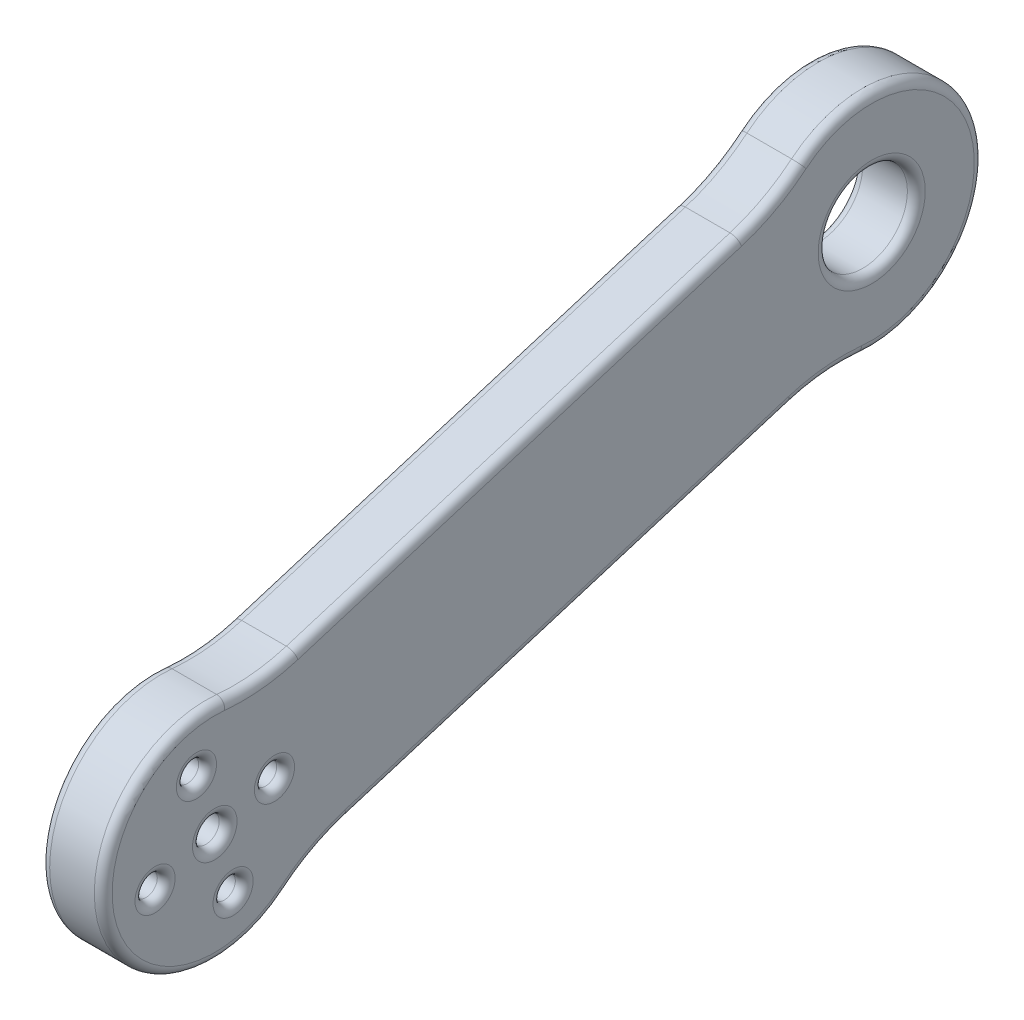
SolidWorks part; units mm, degrees
ref_plane "Front Plane" through (0, 0, 0) normal (1, 0, 0) x (0, 1, 0)
ref_plane "Top Plane" through (0, 0, 0) normal (0, 0, 1) x (0, 1, 0)
ref_plane "Right Plane" through (0, 0, 0) normal (0, 1, 0) x (-1, 0, 0)
sketch "Sketch1" plane through (0, 0, 0) normal (1, 0, 0) x (0, 1, 0)
  line L0 (-11.6048, -20) -> (24.9519, -20)
  line L1 (84.9519, 40) -> (84.9519, 57.8005)
  line L4 (-38.5328, 56.8878) -> (-47.7982, 43.6554)
  line L5 (64.9519, 37.5) -> (87.5414, -36.1119)
  line L6 (87.5414, -36.1119) -> (67.3498, -81.8536)
  line L7 (67.3498, -81.8536) -> (4.2234, -204.9062)
  line L8 (67.3498, -81.8536) -> (0, 0)
  line L9 (0, 0) -> (64.9519, 37.5) construction
  line L11 (-49.5322, 36.7009) -> (-46.3439, 10.7346)
  line L12 (-32.0778, 61.0001) -> (61.4789, 77.4967)
  arc A0 (24.9519, -20) -> (84.9519, 40) centre (24.9519, 40) ccw
  arc A1 (84.9519, 57.8005) -> (61.4789, 77.4967) centre (64.9519, 57.8005) ccw
  circle A3 centre (0, 0) radius 5
  circle A4 centre (0, 0) radius 10
  circle A5 centre (64.9519, 37.5) radius 5
  circle A6 centre (64.9519, 37.5) radius 10
  circle A7 centre (87.5414, -36.1119) radius 5
  circle A8 centre (87.5414, -36.1119) radius 10
  circle A9 centre (67.3498, -81.8536) radius 5
  circle A10 centre (67.3498, -81.8536) radius 10
  circle A11 centre (4.2234, -204.9062) radius 10
  circle A12 centre (4.2234, -204.9062) radius 50
  arc A13 (-46.3439, 10.7346) -> (-11.6048, -20) centre (-11.6048, 15) ccw
  arc A14 (-47.7982, 43.6554) -> (-49.5322, 36.7009) centre (-39.6067, 37.9196) ccw
  arc A16 (-32.0778, 61.0001) -> (-38.5328, 56.8878) centre (-30.3413, 51.152) ccw
  dimension "D3" = 60
  dimension "D16" = 20
  dimension "D17" = 10
  dimension "D18" = 20
  dimension "D19" = 100
  dimension "D22" = 35
  dimension "D24" = 10
  dimension "D7" = 10
  dimension "D1" = 20
  dimension "D4" = 20
  dimension "D5" = 95
  dimension "D9" = 10
  dimension "D10" = 75
  dimension "D11" = 77
  dimension "D12" = 50
  dimension "D13" = 138.3
  dimension "D14" = 3.34
  dimension "D15" = 30
  dimension "D20" = 106
sketch "Sketch3" plane through (0, 0, 0) normal (1, 0, 0) x (0, 1, 0)
  line L1 (74.3143, -27.0956) -> (59.059, 22.6163)
  line L2 (78.179, 28.4837) -> (93.4343, -21.2282)
  line L3 (64.9519, 37.5) -> (87.5414, -36.1119) construction
  line L4 (58.2599, 35.4464) -> (71.6439, 39.5536) construction
  line L5 (62.8983, 44.192) -> (67.0055, 30.808) construction
  arc A0 (77.3931, 36.2889) -> (55.3316, 29.5188) centre (64.9519, 37.5) ccw
  arc A1 (75.1002, -34.9008) -> (97.1617, -28.1307) centre (87.5414, -36.1119) ccw
  circle A2 centre (87.5414, -36.1119) radius 10 construction
  arc A3 (77.3931, 36.2889) -> (78.179, 28.4837) centre (97.299, 34.3511) ccw
  circle A5 centre (87.5414, -36.1119) radius 5
  circle A6 centre (87.5414, -36.1119) radius 10 construction
  circle A7 centre (64.9519, 37.5) radius 10 construction
  arc A9 (93.4343, -21.2282) -> (97.1617, -28.1307) centre (112.5542, -15.3608) ccw
  arc A10 (74.3143, -27.0956) -> (75.1002, -34.9008) centre (55.1943, -32.963) cw
  arc A11 (55.3316, 29.5188) -> (59.059, 22.6163) centre (39.9391, 16.7489) cw
  circle A12 centre (64.9519, 37.5) radius 7 construction
  circle A13 centre (62.8983, 44.192) radius 1.25
  circle A14 centre (71.6439, 39.5536) radius 1.25
  circle A15 centre (67.0055, 30.808) radius 1.25
  circle A16 centre (58.2599, 35.4464) radius 1.25
  circle A17 centre (64.9519, 37.5) radius 1.5
  dimension "D1" = 10
  dimension "D2" = 77
  dimension "D3" = 10
  dimension "D4" = 25
  dimension "D5" = 20
  dimension "D6" = 2.5
  dimension "D7" = 3
  dimension "D8" = 14
extrude "Boss-Extrude2" add sketch "Sketch3" along normal blind 7
fillet "Fillet2" radius 1 28 edges at (0, 87.5414, -41.1119) (0, 66.6867, -2.2397) (7, 87.5414, -41.1119) (7, 66.6867, -2.2397) (0, 61.2848, 49.45) (0, 57.5371, 26.2521) (0, 75.0937, -30.9593) (0, 91.2085, -48.0619) (0, 94.9562, -24.864) (0, 85.8066, 3.6277) (0, 77.3996, 32.3474) (7, 85.8066, 3.6277) (7, 94.9562, -24.864) (7, 91.2085, -48.0619) (7, 75.0937, -30.9593) (7, 57.5371, 26.2521) (7, 61.2848, 49.45) (7, 77.3996, 32.3474) (0, 64.9519, 36) (0, 58.2599, 34.1964) (0, 67.0055, 29.558) (0, 71.6439, 38.3036) (0, 62.8983, 42.942) (7, 64.9519, 36) (7, 67.0055, 29.558) (7, 62.8983, 42.942) (7, 71.6439, 38.3036) (7, 58.2599, 34.1964)
